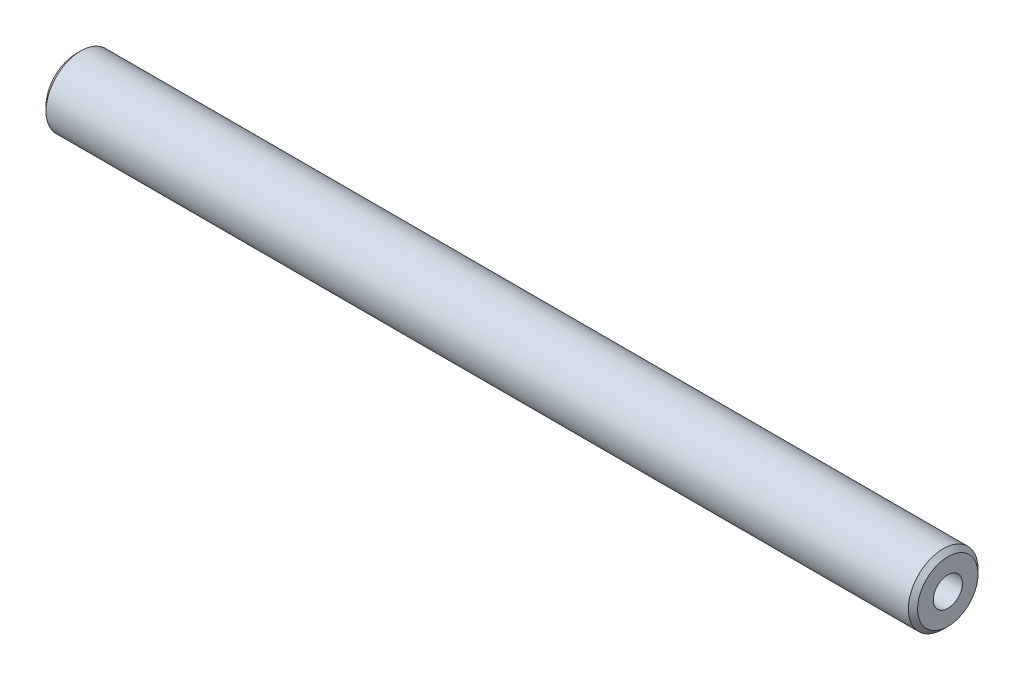
SolidWorks part; units mm, degrees
material "A2017-T4"
ref_plane "Front Plane" through (0, 0, 0) normal (0, 0, 1) x (1, 0, 0)
ref_plane "Top Plane" through (0, 0, 0) normal (0, 1, 0) x (1, 0, 0)
ref_plane "Right Plane" through (0, 0, 0) normal (1, 0, 0) x (0, 0, -1)
sketch "Sketch1" plane through (0, 0, 0) normal (0, 0, 1) x (1, 0, 0)
  line L0 (0, 3) -> (75, 3)
  line L1 (0, 0) -> (75, 0)
  line L2 (0, 3) -> (0, 0)
  line L3 (0, 0) -> (75, 0) construction
  line L4 (75, 3) -> (75, 0)
  dimension "L" = 75
  dimension "D" = 6
revolve "Revolve1" add sketch "Sketch1" angle 360 about L1
chamfer "Chamfer1" distance 0.4 angle 45 2 edges at (75, 0, 3) (0, 0, 3)
ref_plane "Dim. SC" through (6, 0, 0) normal (1, 0, 0) x (0, 0, -1)
hole_wizard "Tapped Hole1" [suppressed] positions "Sketch3" profile "Sketch2" tap size "M4x0.7" standard "JIS"
sketch "Sketch3" [suppressed] plane through (0, 0, 0) normal (-1, 0, 0) x (0, 0, 1)
  point P0 (0, 0)
sketch "Sketch2" [suppressed] plane through (0, 0, 0) normal (0, 1, 0) x (0, 0, 1)
  line L0 (0, 0) -> (0, 12.4914)
  line L1 (0, 12.4914) -> (1.65, 11.5)
  line L2 (1.65, 11.5) -> (1.65, 0)
  line L3 (2, 0) -> (2, 11.5) construction
  line L5 (1.65, 0) -> (0, 0)
  line L10 (0, 12.4914) -> (-1.65, 11.5) construction
  line L11 (0, 0) -> (0, 12.4914) construction
  dimension "Tap Drill Dia." = 3.3
  dimension "Tap Drill Depth" = 11.5
  dimension "Drill Angle" = 118
  dimension "M" = 3
cosmetic thread "Hole Thread1" [suppressed] parameters "Mx2"=8, "M"=3
hole_wizard "Tapped Hole2" [suppressed] positions "Sketch5" profile "Sketch4" tap size "M4x0.7" standard "JIS"
sketch "Sketch5" [suppressed] plane through (30, 0, 0) normal (1, 0, 0) x (0, 0, -1)
  point P0 (0, 0)
sketch "Sketch4" [suppressed] plane through (30, 0, 0) normal (0, 1, 0) x (0, 0, -1)
  line L0 (0, 0) -> (0, 12.4914)
  line L1 (0, 12.4914) -> (1.65, 11.5)
  line L2 (1.65, 11.5) -> (1.65, 0)
  line L5 (1.65, 0) -> (0, 0)
  line L10 (0, 12.4914) -> (-1.65, 11.5) construction
  line L11 (0, 0) -> (0, 12.4914) construction
  dimension "Tap Drill Dia." = 3.3
  dimension "Tap Drill Depth" = 11.5
  dimension "Drill Angle" = 118
cosmetic thread "Hole Thread2" [suppressed] parameters "Mx2"=8, "M"=3
hole_wizard "Tapped Hole3" [suppressed] positions "Sketch7" profile "Sketch6" tap size "M4x0.7" standard "JIS"
sketch "Sketch7" [suppressed] plane through (0, 0, 0) normal (-1, 0, 0) x (0, 0, 1)
  point P0 (0, 0)
sketch "Sketch6" [suppressed] plane through (0, 0, 0) normal (0, 1, 0) x (0, 0, 1)
  line L0 (0, 0) -> (0, 30)
  line L1 (0, 30) -> (1.65, 30)
  line L2 (1.65, 30) -> (1.65, 0)
  line L5 (1.65, 0) -> (0, 0)
  line L11 (0, 0) -> (0, 30) construction
  dimension "Thru Tap Drill Dia." = 3.3
  dimension "Thru Tap Drill Depth" = 30
cosmetic thread "Hole Thread3" [suppressed] parameters "M"=3
sketch "Sketch8" [suppressed] plane through (0, 0, 0) normal (0, 1, 0) x (1, 0, 0)
  line L0 (10, -3.5) -> (10, -4) construction
  line L1 (6, 4) -> (14, 4)
  line L2 (6, 4) -> (6, 3.5)
  line L3 (6, 3.5) -> (14, 3.5)
  line L4 (14, 4) -> (14, 3.5)
  line L5 (6, -3.5) -> (14, -3.5)
  line L6 (6, -3.5) -> (6, -4)
  line L7 (6, -4) -> (14, -4)
  line L8 (14, -3.5) -> (14, -4)
  line L12 (0, 0) -> (30, 0) construction
  dimension "S" = 6
  dimension "W" = 7
  dimension "L1_s" = 8
  dimension "D" = 6
  dimension "L1_s_L" = 8
extrude "Cut-Extrude1" [suppressed] cut sketch "Sketch8" against normal through all and the other way through all
ref_plane "L Dimension Selectable_SEC" [suppressed] through (10, 0, 0) normal (1, 0, 0) x (0, 0, -1)
hole_wizard "Tapped Hole4" [suppressed] positions "Sketch10" profile "Sketch9" tap size "M4x0.7" standard "JIS"
sketch "Sketch10" [suppressed] plane through (0, 0, 0) normal (-1, 0, 0) x (0, 0, 1)
  point P0 (0, 0)
sketch "Sketch9" [suppressed] plane through (0, 0, 0) normal (0, 1, 0) x (0, 0, 1)
  line L0 (0, 0) -> (0, 12.4914)
  line L1 (0, 12.4914) -> (1.65, 11.5)
  line L2 (1.65, 11.5) -> (1.65, 0)
  line L3 (2, 0) -> (2, 11.5) construction
  line L5 (1.65, 0) -> (0, 0)
  line L10 (0, 12.4914) -> (-1.65, 11.5) construction
  line L11 (0, 0) -> (0, 12.4914) construction
  dimension "Tap Drill Dia." = 3.3
  dimension "Tap Drill Depth" = 11.5
  dimension "Drill Angle" = 118
  dimension "M" = 3
cosmetic thread "Hole Thread4" [suppressed] parameters "Mx2"=8, "M"=3
hole_wizard "Tapped Hole5" [suppressed] positions "Sketch12" profile "Sketch11" tap size "M4x0.7" standard "JIS"
sketch "Sketch12" [suppressed] plane through (30, 0, 0) normal (1, 0, 0) x (0, 0, -1)
  point P0 (0, 0)
sketch "Sketch11" [suppressed] plane through (30, 0, 0) normal (0, 1, 0) x (0, 0, -1)
  line L0 (0, 0) -> (0, 12.4914)
  line L1 (0, 12.4914) -> (1.65, 11.5)
  line L2 (1.65, 11.5) -> (1.65, 0)
  line L5 (1.65, 0) -> (0, 0)
  line L10 (0, 12.4914) -> (-1.65, 11.5) construction
  line L11 (0, 0) -> (0, 12.4914) construction
  dimension "Tap Drill Dia." = 3.3
  dimension "Tap Drill Depth" = 11.5
  dimension "Drill Angle" = 118
cosmetic thread "Hole Thread5" [suppressed] parameters "Mx2"=8, "M"=3
hole_wizard "Tapped Hole6" [suppressed] positions "Sketch14" profile "Sketch13" tap size "M4x0.7" standard "JIS"
sketch "Sketch14" [suppressed] plane through (0, 0, 0) normal (-1, 0, 0) x (0, 0, 1)
  point P0 (0, 0)
sketch "Sketch13" [suppressed] plane through (0, 0, 0) normal (0, 1, 0) x (0, 0, 1)
  line L0 (0, 0) -> (0, 30)
  line L1 (0, 30) -> (1.65, 30)
  line L2 (1.65, 30) -> (1.65, 0)
  line L5 (1.65, 0) -> (0, 0)
  line L11 (0, 0) -> (0, 30) construction
  dimension "Thru Tap Drill Dia." = 3.3
  dimension "Thru Tap Drill Depth" = 30
cosmetic thread "Hole Thread6" [suppressed] parameters "M"=3
hole_wizard "Tapped Hole7" [suppressed] positions "Sketch16" profile "Sketch15" tap size "M4x0.7" standard "JIS"
sketch "Sketch16" [suppressed] plane through (0, 0, 0) normal (-1, 0, 0) x (0, 0, 1)
  point P0 (0, 0)
sketch "Sketch15" [suppressed] plane through (0, 0, 0) normal (0, 1, 0) x (0, 0, 1)
  line L0 (0, 0) -> (0, 12.4914)
  line L1 (0, 12.4914) -> (1.65, 11.5)
  line L2 (1.65, 11.5) -> (1.65, 0)
  line L3 (2, 0) -> (2, 11.5) construction
  line L5 (1.65, 0) -> (0, 0)
  line L10 (0, 12.4914) -> (-1.65, 11.5) construction
  line L11 (0, 0) -> (0, 12.4914) construction
  dimension "Tap Drill Dia." = 3.3
  dimension "Tap Drill Depth" = 11.5
  dimension "Drill Angle" = 118
  dimension "M" = 3
cosmetic thread "Hole Thread7" [suppressed] parameters "Mx2"=8, "M"=3
hole_wizard "Tapped Hole8" [suppressed] positions "Sketch18" profile "Sketch17" tap size "M4x0.7" standard "JIS"
sketch "Sketch18" [suppressed] plane through (30, 0, 0) normal (1, 0, 0) x (0, 0, -1)
  point P0 (0, 0)
sketch "Sketch17" [suppressed] plane through (30, 0, 0) normal (0, 1, 0) x (0, 0, -1)
  line L0 (0, 0) -> (0, 12.4914)
  line L1 (0, 12.4914) -> (1.65, 11.5)
  line L2 (1.65, 11.5) -> (1.65, 0)
  line L5 (1.65, 0) -> (0, 0)
  line L10 (0, 12.4914) -> (-1.65, 11.5) construction
  line L11 (0, 0) -> (0, 12.4914) construction
  dimension "Tap Drill Dia." = 3.3
  dimension "Tap Drill Depth" = 11.5
  dimension "Drill Angle" = 118
cosmetic thread "Hole Thread8" [suppressed] parameters "Mx2"=8, "M"=3
hole_wizard "Tapped Hole9" [suppressed] positions "Sketch20" profile "Sketch19" tap size "M4x0.7" standard "JIS"
sketch "Sketch20" [suppressed] plane through (0, 0, 0) normal (-1, 0, 0) x (0, 0, 1)
  point P0 (0, 0)
sketch "Sketch19" [suppressed] plane through (0, 0, 0) normal (0, 1, 0) x (0, 0, 1)
  line L0 (0, 0) -> (0, 30)
  line L1 (0, 30) -> (1.65, 30)
  line L2 (1.65, 30) -> (1.65, 0)
  line L5 (1.65, 0) -> (0, 0)
  line L11 (0, 0) -> (0, 30) construction
  dimension "Thru Tap Drill Dia." = 3.3
  dimension "Thru Tap Drill Depth" = 30
cosmetic thread "Hole Thread9" [suppressed] parameters "M"=3
sketch "Sketch21" [suppressed] plane through (0, 0, 0) normal (0, 1, 0) x (1, 0, 0)
  line L0 (0, 0) -> (30, 0) construction
  line L1 (6, 4) -> (14, 4)
  line L2 (6, 4) -> (6, 3.5)
  line L3 (6, 3.5) -> (14, 3.5)
  line L4 (14, 4) -> (14, 3.5)
  line L5 (6, -3.5) -> (14, -3.5)
  line L6 (6, -3.5) -> (6, -4)
  line L7 (6, -4) -> (14, -4)
  line L8 (14, -3.5) -> (14, -4)
  line L9 (10, -3.5) -> (10, -4) construction
  line L18 (6, -4.4) -> (6, 4.4) construction
  line L19 (30, -3.6) -> (30, 3.6) construction
  dimension "W" = 7
  dimension "L1_s" = 8
  dimension "D" = 6
  dimension "L1_s_L" = 8
extrude "Cut-Extrude2" [suppressed] cut sketch "Sketch21" against normal through all and the other way through all
ref_plane "L Dimension Cofigurable, Wrench Flats_SEC" [suppressed] through (10, 0, 0) normal (1, 0, 0) x (0, 0, -1)
hole_wizard "Tapped Hole10" positions "Sketch23" profile "Sketch22" tap size "M4x0.7" standard "JIS"
sketch "Sketch23" plane through (0, 0, 0) normal (-1, 0, 0) x (0, 0, 1)
  point P0 (0, 0)
sketch "Sketch22" plane through (0, 0, 0) normal (0, 1, 0) x (0, 0, 1)
  line L0 (0, 0) -> (0, 9.2511)
  line L1 (0, 9.2511) -> (1.25, 8.5)
  line L2 (1.25, 8.5) -> (1.25, 0)
  line L3 (1.5, 0) -> (1.5, 8.5) construction
  line L5 (1.25, 0) -> (0, 0)
  line L10 (0, 9.2511) -> (-1.25, 8.5) construction
  line L11 (0, 0) -> (0, 9.2511) construction
  dimension "Tap Drill Dia." = 2.5
  dimension "Tap Drill Depth" = 8.5
  dimension "Drill Angle" = 118
  dimension "M" = 3
  dimension "Pilot hole Tip" = 9.2511
cosmetic thread "Hole Thread10" parameters "Mx2"=6, "M"=3
hole_wizard "Tapped Hole11" positions "Sketch25" profile "Sketch24" tap size "M4x0.7" standard "JIS"
sketch "Sketch25" plane through (75, 0, 0) normal (1, 0, 0) x (0, 0, -1)
  point P0 (0, 0)
sketch "Sketch24" plane through (75, 0, 0) normal (0, 1, 0) x (0, 0, -1)
  line L0 (0, 9.2511) -> (0, 0)
  line L1 (0, 9.2511) -> (1.25, 8.5)
  line L2 (1.25, 8.5) -> (1.25, 0)
  line L3 (1.5, 8.5) -> (1.5, 0) construction
  line L5 (1.25, 0) -> (0, 0)
  line L10 (0, 9.2511) -> (-1.25, 8.5) construction
  line L11 (0, 0) -> (0, 9.2511) construction
  dimension "Tap Drill Dia." = 2.5
  dimension "Tap Drill Depth" = 8.5
  dimension "Drill Angle" = 118
  dimension "N" = 3
  dimension "Pilot hole Tip" = 9.2511
cosmetic thread "Hole Thread11" parameters "Nx2"=6, "N"=3
sketch "Sketch26" plane through (0, 0, 0) normal (-1, 0, 0) x (0, 0, 1)
  circle A0 centre (0, 0) radius 1.25
  circle A1 centre (0, 0) radius 1.25
  dimension "MSM_1" = 2.5
  dimension "MSM_2" = 2.5
extrude "Boss-Extrude1" [suppressed] add sketch "Sketch26" against normal blind 6
sketch "Sketch27" plane through (75, 0, 0) normal (1, 0, 0) x (0, 0, -1)
  circle A0 centre (0, 0) radius 1.25
  circle A1 centre (0, 0) radius 1.25
  dimension "MSM_2" = 2.5
  dimension "MSM_1" = 2.5
extrude "Boss-Extrude2" [suppressed] add sketch "Sketch27" against normal blind 6
hole_wizard "Tapped Hole12" [suppressed] positions "Sketch29" profile "Sketch28" tap size "M4x0.7" standard "JIS"
sketch "Sketch29" [suppressed] plane through (0, 0, 0) normal (-1, 0, 0) x (0, 0, 1)
  point P0 (0, 0)
sketch "Sketch28" [suppressed] plane through (0, 0, 0) normal (0, 1, 0) x (0, 0, 1)
  line L0 (0, 0) -> (0, 12.4914)
  line L1 (0, 12.4914) -> (1.65, 11.5)
  line L2 (1.65, 11.5) -> (1.65, 0)
  line L3 (2, 0) -> (2, 11.5) construction
  line L5 (1.65, 0) -> (0, 0)
  line L10 (0, 12.4914) -> (-1.65, 11.5) construction
  line L11 (0, 0) -> (0, 12.4914) construction
  dimension "Tap Drill Dia." = 3.3
  dimension "Tap Drill Depth" = 11.5
  dimension "Drill Angle" = 118
  dimension "M" = 3
  dimension "Pilot hole Tip" = 12.4914
cosmetic thread "Hole Thread12" [suppressed] parameters "Mx2"=8, "M"=3
hole_wizard "Tapped Hole13" [suppressed] positions "Sketch31" profile "Sketch30" tap size "M4x0.7" standard "JIS"
sketch "Sketch31" [suppressed] plane through (30, 0, 0) normal (1, 0, 0) x (0, 0, -1)
  point P0 (0, 0)
sketch "Sketch30" [suppressed] plane through (30, 0, 0) normal (0, 1, 0) x (0, 0, -1)
  line L0 (0, 12.4914) -> (0, 0)
  line L1 (0, 12.4914) -> (1.65, 11.5)
  line L2 (1.65, 11.5) -> (1.65, 0)
  line L3 (2, 11.5) -> (2, 0) construction
  line L5 (1.65, 0) -> (0, 0)
  line L10 (0, 12.4914) -> (-1.65, 11.5) construction
  line L11 (0, 0) -> (0, 12.4914) construction
  dimension "Tap Drill Dia." = 3.3
  dimension "Tap Drill Depth" = 11.5
  dimension "Drill Angle" = 118
  dimension "N" = 3
  dimension "Pilot hole Tip" = 12.4914
cosmetic thread "Hole Thread13" [suppressed] parameters "Nx2"=8, "N"=3
sketch "Sketch32" [suppressed] plane through (0, 0, 0) normal (-1, 0, 0) x (0, 0, 1)
  circle A0 centre (0, 0) radius 1.65
  circle A1 centre (0, 0) radius 1.65
  dimension "MSM_2" = 2.5
  dimension "MSM_1" = 2.5
extrude "Boss-Extrude3" [suppressed] add sketch "Sketch32" against normal blind 6
sketch "Sketch33" [suppressed] plane through (30, 0, 0) normal (1, 0, 0) x (0, 0, -1)
  circle A0 centre (0, 0) radius 1.65
  circle A1 centre (0, 0) radius 1.65
  dimension "MSM_1" = 2.5
  dimension "MSM_2" = 2.5
extrude "Boss-Extrude4" [suppressed] add sketch "Sketch33" against normal blind 6
sketch "Sketch34" [suppressed] plane through (0, 0, 0) normal (0, 1, 0) x (1, 0, 0)
  line L0 (10, -3.5) -> (10, -4) construction
  line L1 (6, 4) -> (14, 4)
  line L2 (6, 4) -> (6, 3.5)
  line L3 (6, 3.5) -> (14, 3.5)
  line L4 (14, 4) -> (14, 3.5)
  line L5 (6, -3.5) -> (14, -3.5)
  line L6 (6, -3.5) -> (6, -4)
  line L7 (6, -4) -> (14, -4)
  line L8 (14, -3.5) -> (14, -4)
  line L9 (30, -3.6) -> (30, 3.6) construction
  line L12 (0, 0) -> (30, 0) construction
  line L15 (6, -4.4) -> (6, 4.4) construction
  dimension "L1_s" = 8
  dimension "W" = 7
  dimension "D" = 6
  dimension "L1_s_L" = 8
extrude "Cut-Extrude3" [suppressed] cut sketch "Sketch34" against normal through all and the other way through all
ref_plane "L Dimension Configurable, Thread Dia. Configurable, Wrench Flats_SEC" [suppressed] through (10, 0, 0) normal (1, 0, 0) x (0, 0, -1)
hole_wizard "Tapped Hole14" [suppressed] positions "Sketch36" profile "Sketch35" tap size "M4x0.7" standard "JIS"
sketch "Sketch36" [suppressed] plane through (0, 0, 0) normal (-1, 0, 0) x (0, 0, 1)
  point P0 (0, 0)
sketch "Sketch35" [suppressed] plane through (0, 0, 0) normal (0, 1, 0) x (0, 0, 1)
  line L0 (0, 0) -> (0, 16.4914)
  line L1 (0, 16.4914) -> (1.65, 15.5)
  line L2 (1.65, 15.5) -> (1.65, 0)
  line L5 (1.65, 0) -> (0, 0)
  line L10 (0, 16.4914) -> (-1.65, 15.5) construction
  line L11 (0, 0) -> (0, 16.4914) construction
  dimension "Tap Drill Dia." = 3.3
  dimension "Tap Drill Depth" = 15.5
  dimension "Drill Angle" = 118
cosmetic thread "Hole Thread14" [suppressed] parameters "Mx3"=12, "MD"=4
hole_wizard "Tapped Hole15" [suppressed] positions "Sketch38" profile "Sketch37" tap size "M4x0.7" standard "JIS"
sketch "Sketch38" [suppressed] plane through (30, -2.1135, -9.2544) normal (1, 0, 0) x (0, 0, -1)
  point P0 (-9.2544, 2.1135)
sketch "Sketch37" [suppressed] plane through (30, 0, 0) normal (0, 1, 0) x (0, 0, -1)
  line L0 (0, 0) -> (0, 16.4914)
  line L1 (0, 16.4914) -> (1.65, 15.5)
  line L2 (1.65, 15.5) -> (1.65, 0)
  line L5 (1.65, 0) -> (0, 0)
  line L10 (0, 16.4914) -> (-1.65, 15.5) construction
  line L11 (0, 0) -> (0, 16.4914) construction
  dimension "Tap Drill Dia." = 3.3
  dimension "Tap Drill Depth" = 15.5
  dimension "Drill Angle" = 118
cosmetic thread "Hole Thread15" [suppressed] parameters "Nx3"=12, "ND"=4
ref_plane "Plane1" [suppressed] through (0, 4, 0) normal (0, 1, 0) x (1, 0, 0)
hole_wizard "Diameter Hole1" [suppressed] positions "Sketch40" profile "Sketch39" hole size "Ø2.5" standard "JIS"
sketch "Sketch40" [suppressed] plane through (0, 4, 0) normal (0, 1, 0) x (1, 0, 0)
  line L0 (0, 3.8) -> (0, -3.8) construction
  point P0 (7, 0)
  dimension "HL" = 7
sketch "Sketch39" [suppressed] plane through (7, 4, 0) normal (1, 0, 0) x (0, 0, 1)
  line L0 (0, 0) -> (0, 8)
  line L1 (0, 8) -> (1.25, 8)
  line L2 (1.25, 8) -> (1.25, 0)
  line L5 (1.25, 0) -> (0, 0)
  line L11 (0, 0) -> (0, 8) construction
  dimension "D_s" = 2.5
  dimension "Thru Hole Depth" = 8
equation "\"Plane dim\"= \"D@Sketch1\" * 0.5"
equation "\"D1@Boss-Extrude1\" = \"M\" * 2"
equation "\"D1@Boss-Extrude2\" = \"N\" * 2"
equation "\"D1@Boss-Extrude3\" = \"M\" * 2"
equation "\"D1@Boss-Extrude4\" = \"N\" * 2"
equation "\"M\"=3"
equation "\"N\"=3"
